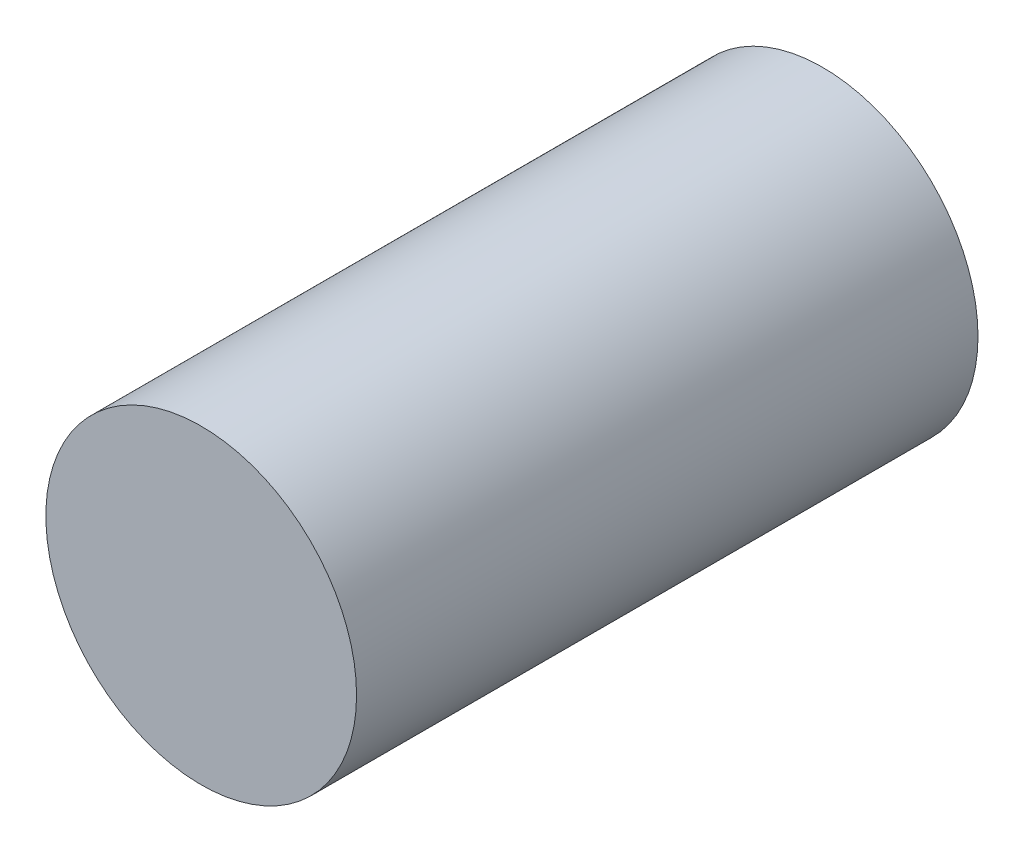
SolidWorks part; units mm, degrees
material "Concreto"
ref_plane "Plano frontal" through (0, 0, 0) normal (0, 0, 1) x (1, 0, 0)
ref_plane "Plano superior" through (0, 0, 0) normal (0, 1, 0) x (1, 0, 0)
ref_plane "Plano direito" through (0, 0, 0) normal (1, 0, 0) x (0, 0, -1)
sketch "Esboço1" plane through (0, 0, 0) normal (0, 0, 1) x (1, 0, 0)
  circle A0 centre (0, 0) radius 50
  dimension "D1" = 100
extrude "Ressalto-extrusão1" add sketch "Esboço1" along normal blind 200
